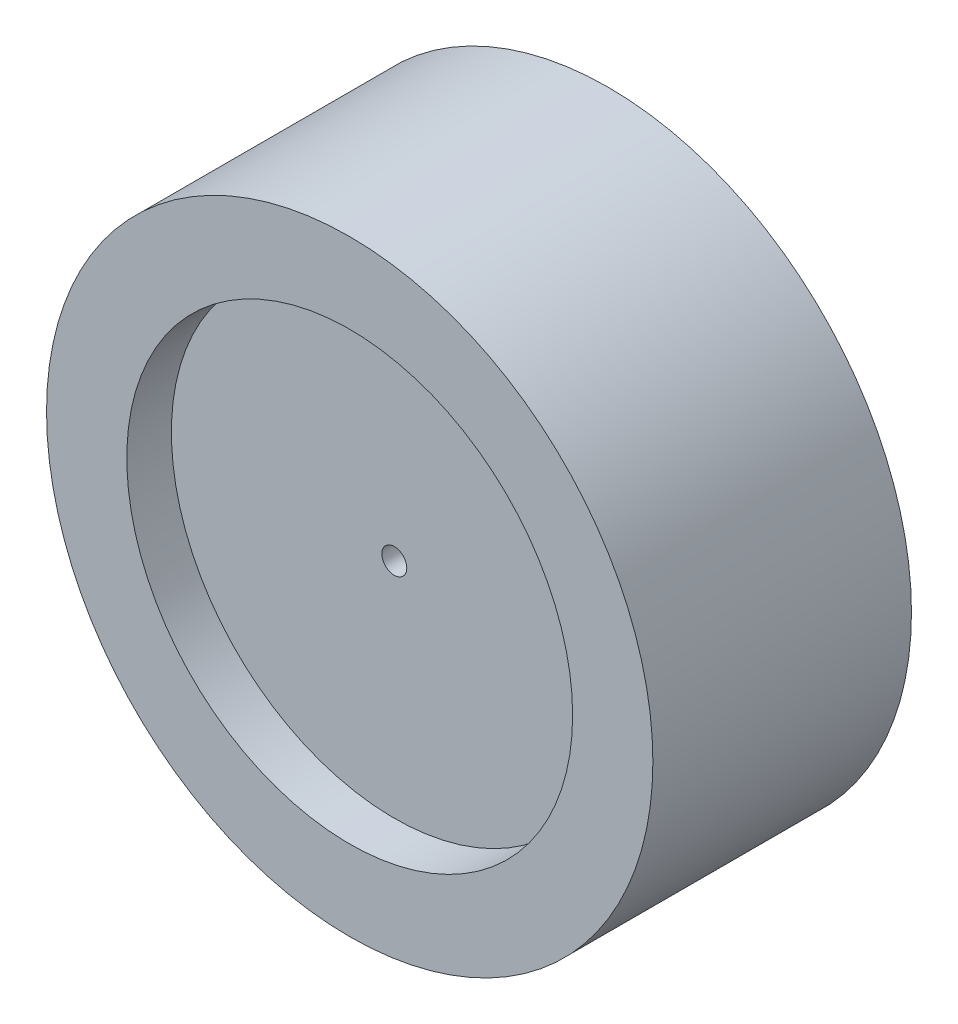
SolidWorks part; units mm, degrees
ref_plane "前视基准面" through (0, 0, 0) normal (0, 0, 1) x (1, 0, 0)
ref_plane "上视基准面" through (0, 0, 0) normal (0, 1, 0) x (1, 0, 0)
ref_plane "右视基准面" through (0, 0, 0) normal (1, 0, 0) x (0, 0, -1)
sketch "草图1" plane through (0, 0, 0) normal (0, 0, 1) x (1, 0, 0)
  circle A0 centre (0, 0) radius 34
  dimension "D1" = 68
extrude "凸台-拉伸1" add sketch "草图1" along normal blind 29
sketch "草图2" plane through (0, 0, 29) normal (0, 0, 1) x (1, 0, 0)
  circle A0 centre (0, 0) radius 25
extrude "切除-拉伸1" cut sketch "草图2" against normal blind 5
sketch "草图3" plane through (0, 0, 0) normal (0, 0, -1) x (-1, 0, 0)
  circle A0 centre (0, 0) radius 25
extrude "切除-拉伸2" cut sketch "草图3" against normal blind 5
sketch "草图4" plane through (0, 0, 5) normal (0, 0, -1) x (-1, 0, 0)
  line L1 (2.3528, -3.1429) -> (3.8982, 0.4661)
  line L2 (3.8982, 0.4661) -> (1.5454, 3.609)
  line L3 (1.5454, 3.609) -> (-2.3528, 3.1429)
  line L4 (-2.3528, 3.1429) -> (-3.8982, -0.4661)
  line L5 (-3.8982, -0.4661) -> (-1.5454, -3.609)
  line L6 (-1.5454, -3.609) -> (2.3528, -3.1429)
  circle A0 centre (0, 0) radius 3.4 construction
  dimension "D1" = 6.8
extrude "切除-拉伸3" cut sketch "草图4" against normal blind 10
sketch "草图5" plane through (0, 0, 24) normal (0, 0, 1) x (1, 0, 0)
  circle A0 centre (0, 0) radius 1.4
  dimension "D1" = 2.8
extrude "切除-拉伸4" cut sketch "草图5" against normal through all
